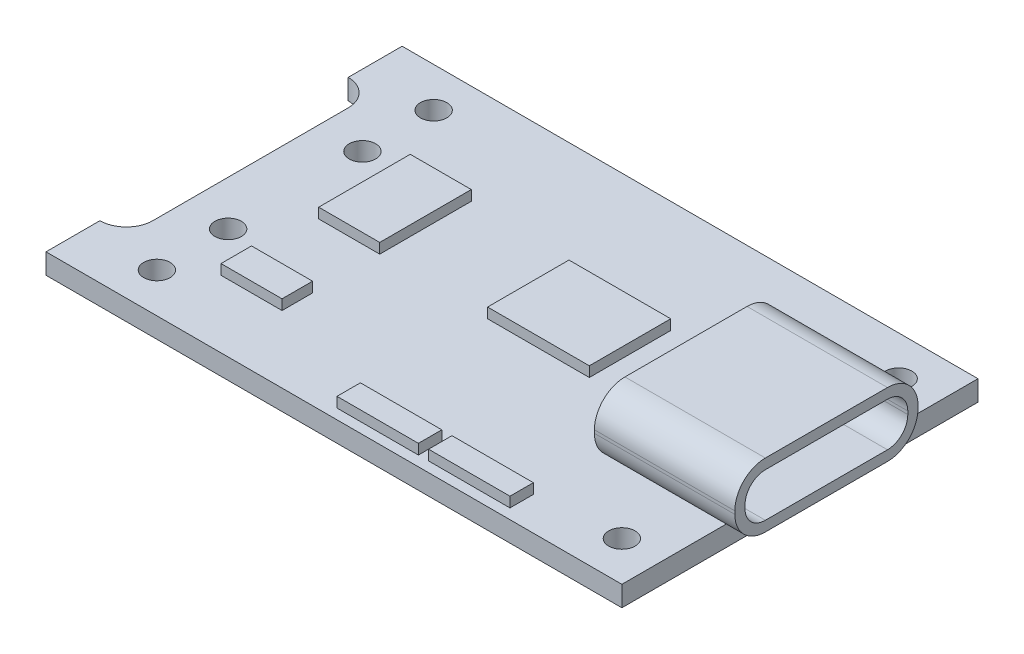
SolidWorks part; units mm, degrees
ref_plane "Alzado" through (0, 0, 0) normal (0, 0, 1) x (1, 0, 0)
ref_plane "Planta" through (0, 0, 0) normal (0, 1, 0) x (1, 0, 0)
ref_plane "Vista lateral" through (0, 0, 0) normal (1, 0, 0) x (0, 0, -1)
sketch "Croquis1" plane through (0, 0, 0) normal (0, 1, 0) x (1, 0, 0)
  line L0 (16.4731, 0) -> (-16.4731, 0) construction
  line L1 (-14.15, 8.75) -> (14.15, 8.75)
  line L2 (-14.15, 8.75) -> (-14.15, -8.75) construction
  line L3 (-14.15, -8.75) -> (14.15, -8.75)
  line L4 (14.15, 8.75) -> (14.15, -8.75)
  line L5 (-14.15, 8.75) -> (14.15, -8.75) construction
  line L6 (-14.15, -8.75) -> (14.15, 8.75) construction
  line L7 (-12.85, 4.8) -> (-12.85, -4.8)
  line L8 (-14.15, 8.75) -> (-14.15, 6.1)
  line L9 (-14.15, -8.75) -> (-14.15, -6.1)
  arc A0 (-14.15, 6.1) -> (-12.85, 4.8) centre (-14.15, 4.8) cw
  arc A1 (-14.15, -6.1) -> (-12.85, -4.8) centre (-14.15, -4.8) ccw
  circle A2 centre (12.2, 6.8) radius 0.65
  circle A3 centre (12.2, -6.8) radius 0.65
  circle A4 centre (-10.65, 6.8) radius 0.65
  circle A5 centre (-10.65, 3.3) radius 0.65
  circle A6 centre (-10.65, -3.3) radius 0.65
  circle A7 centre (-10.65, -6.8) radius 0.65
  point P0 (0, 0)
  point P9 (0, 0)
  point P13 (-12.85, 0)
  point P18 (12.85, 6.8)
  point P20 (12.2, 7.45)
  point P24 (0, 0)
  dimension "D6" = 1.3
  dimension "D1" = 28.3
  dimension "D2" = 17.5
  dimension "D3" = 2.65
  dimension "D4" = 1.3
  dimension "D5" = 1.3
  dimension "D7" = 1.3
  dimension "D8" = 3.5
  dimension "D9" = 3.5
extrude "Saliente-Extruir1" add sketch "Croquis1" along normal blind 1
sketch "Croquis2" plane through (0, 1, 0) normal (0, 1, 0) x (1, 0, 0)
  line L0 (14.15, -8.75) -> (14.15, 8.75) construction
  line L1 (8.55, 4.5) -> (15.45, 4.5)
  line L2 (8.55, 4.5) -> (8.55, -4.5)
  line L3 (8.55, -4.5) -> (15.45, -4.5)
  line L4 (15.45, 4.5) -> (15.45, -4.5)
  point P4 (8.55, 0)
  point P6 (9.7356, 4.5)
  dimension "D1" = 6.9
  dimension "D2" = 9
  dimension "D3" = 1.3
extrude "Saliente-Extruir2" add sketch "Croquis2" along normal blind 3.15 separate body
fillet "Redondeo1" radius 1.5 4 edges at (12, 1, -4.5) (12, 1, 4.5) (12, 4.15, 4.5) (12, 4.15, -4.5)
shell "Vaciado1" thickness 0.5
sketch "Croquis3" plane through (0, 1, 0) normal (0, 1, 0) x (1, 0, 0)
  line L0 (14.15, -8.75) -> (14.15, 8.75) construction
  line L1 (-0.35, -7.1) -> (3.65, -7.1)
  line L2 (-0.35, -7.1) -> (-0.35, -8.25)
  line L3 (-0.35, -8.25) -> (3.65, -8.25)
  line L4 (3.65, -7.1) -> (3.65, -8.25)
  line L5 (4.15, -7.1) -> (8.15, -7.1)
  line L6 (4.15, -7.1) -> (4.15, -8.25)
  line L7 (4.15, -8.25) -> (8.15, -8.25)
  line L8 (8.15, -7.1) -> (8.15, -8.25)
  line L9 (-14.15, -8.75) -> (14.15, -8.75) construction
  dimension "D1" = 1.15
  dimension "D2" = 4
  dimension "D3" = 6
  dimension "D4" = 0.5
  dimension "D5" = 0.5
extrude "Saliente-Extruir3" add sketch "Croquis3" along normal blind 0.5 separate body
sketch "Croquis4" plane through (0, 1, 0) normal (0, 1, 0) x (1, 0, 0)
  line L0 (8.55, 3) -> (8.55, -3) construction
  line L1 (-8.85, -3.95) -> (-5.85, -3.95)
  line L2 (-8.85, -3.95) -> (-8.85, -5.45)
  line L3 (-8.85, -5.45) -> (-5.85, -5.45)
  line L4 (-5.85, -3.95) -> (-5.85, -5.45)
  line L5 (-8.85, 3.85) -> (-5.85, 3.85)
  line L6 (-8.85, 3.85) -> (-8.85, -0.65)
  line L7 (-8.85, -0.65) -> (-5.85, -0.65)
  line L8 (-5.85, 3.85) -> (-5.85, -0.65)
  line L9 (-0.45, 3.25) -> (4.55, 3.25)
  line L10 (-0.45, 3.25) -> (-0.45, -0.75)
  line L11 (-0.45, -0.75) -> (4.55, -0.75)
  line L12 (4.55, 3.25) -> (4.55, -0.75)
  line L13 (14.15, 8.75) -> (-14.15, 8.75) construction
  line L14 (-14.15, -8.75) -> (14.15, -8.75) construction
  line L15 (-12.85, 4.8) -> (-12.85, -4.8) construction
  dimension "D1" = 4
  dimension "D2" = 5.5
  dimension "D3" = 5
  dimension "D4" = 4
  dimension "D5" = 1.5
  dimension "D6" = 3
  dimension "D7" = 4.5
  dimension "D8" = 3.3
  dimension "D9" = 3.3
  dimension "D10" = 4
extrude "Saliente-Extruir4" add sketch "Croquis4" along normal blind 0.5 separate body
